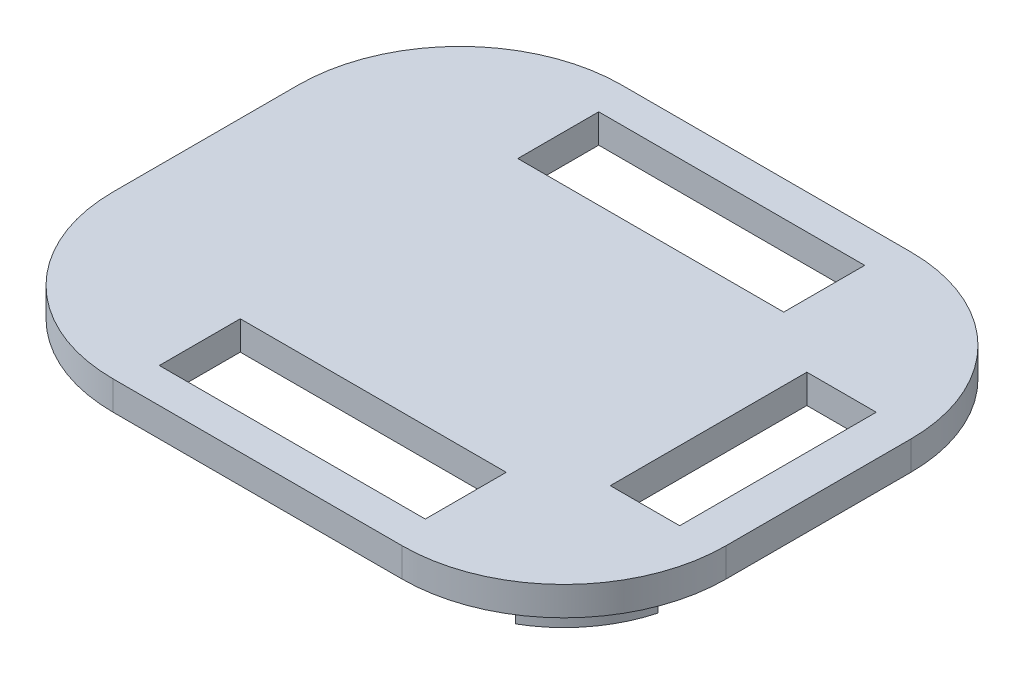
SolidWorks part; units mm, degrees
ref_plane "Front Plane" through (0, 0, 0) normal (0, 0, 1) x (1, 0, 0)
ref_plane "Top Plane" through (0, 0, 0) normal (0, 1, 0) x (1, 0, 0)
ref_plane "Right Plane" through (0, 0, 0) normal (1, 0, 0) x (0, 0, -1)
sketch "Sketch1" plane through (0, 0, 0) normal (0, 1, 0) x (1, 0, 0)
  line L4 (-26.5, 8) -> (-26.5, -8) construction
  line L6 (26.5, -8) -> (26.5, 8) construction
  line L8 (-6.9007, 0) -> (7.9319, 0) construction
  line L9 (0, 7.9961) -> (0, -5.1117) construction
  line L10 (-11.5, -12) -> (11.5, -12)
  line L11 (17, 8.5) -> (23, 8.5)
  line L12 (17, 8.5) -> (17, -8.5)
  line L13 (17, -8.5) -> (23, -8.5)
  line L14 (23, 8.5) -> (23, -8.5)
  line L15 (17, 8.5) -> (23, -8.5) construction
  line L16 (17, -8.5) -> (23, 8.5) construction
  line L17 (-11.5, 19) -> (11.5, 19)
  line L18 (-11.5, 19) -> (-11.5, 12)
  line L19 (-11.5, 12) -> (11.5, 12)
  line L20 (11.5, 19) -> (11.5, 12)
  line L21 (-11.5, 19) -> (11.5, 12) construction
  line L22 (-11.5, 12) -> (11.5, 19) construction
  line L23 (11.5, -19) -> (11.5, -12)
  line L24 (-11.5, -19) -> (11.5, -19)
  line L25 (-11.5, -19) -> (-11.5, -12)
  line L26 (-26.5, 8) -> (-26.5, -8)
  line L27 (-12.5, -22) -> (12.5, -22)
  line L28 (26.5, -8) -> (26.5, 8)
  line L29 (12.5, 22) -> (-12.5, 22)
  arc A6 (12.5, -22) -> (26.5, -8) centre (12.5, -8) ccw construction
  arc A7 (26.5, 8) -> (12.5, 22) centre (12.5, 8) ccw construction
  arc A8 (-12.5, 22) -> (-26.5, 8) centre (-12.5, 8) ccw
  arc A9 (-26.5, -8) -> (-12.5, -22) centre (-12.5, -8) ccw
  arc A10 (12.5, -22) -> (26.5, -8) centre (12.5, -8) ccw
  arc A11 (26.5, 8) -> (12.5, 22) centre (12.5, 8) ccw
  point P3 (26.5, 0)
  point P29 (20, 0)
  point P34 (0, 15.5)
  dimension "D3" = 16
  dimension "D4" = 14
  dimension "D2" = 25
  dimension "D7" = 17
  dimension "D8" = 6
  dimension "D9" = 20
  dimension "D10" = 23
  dimension "D11" = 7
  dimension "D12" = 15.5
extrude "Boss-Extrude1" add sketch "Sketch1" along normal blind 2.5
sketch "Sketch2" plane through (0, 0, 0) normal (0, -1, 0) x (1, 0, 0)
  line L0 (-12.5, -19.5) -> (12.5, -19.5) construction
  line L1 (24, -8) -> (24, 8) construction
  line L2 (12.5, 19.5) -> (-12.5, 19.5) construction
  line L3 (-24, 8) -> (-24, -8) construction
  line L4 (-12.5, -22) -> (12.5, -22)
  line L5 (26.5, -8) -> (26.5, 8)
  line L6 (12.5, 22) -> (-12.5, 22)
  line L7 (-26.5, 8) -> (-26.5, -8)
  line L8 (-12.5, -22) -> (12.5, -22) construction
  line L9 (26.5, -8) -> (26.5, 8) construction
  line L10 (12.5, 22) -> (-12.5, 22) construction
  line L11 (-26.5, 8) -> (-26.5, -8) construction
  line L12 (-12.5, -17) -> (12.5, -17) construction
  line L13 (21.5, -8) -> (21.5, 8) construction
  line L14 (12.5, 17) -> (-12.5, 17) construction
  line L15 (-21.5, 8) -> (-21.5, -8) construction
  line L16 (-17, 15.7942) -> (-18.25, 17.9593)
  line L17 (0, 7.0039) -> (0, -4.9946) construction
  line L18 (-8.9558, 0) -> (14.467, 0) construction
  line L19 (-23.6081, 10.9764) -> (-21.1933, 10.3294)
  line L20 (-12.5, 8) -> (-17, 15.7942) construction
  line L21 (-21.1933, 10.3294) -> (-12.5, 8) construction
  line L22 (23.6081, 10.9764) -> (21.1933, 10.3294)
  line L23 (17, 15.7942) -> (18.25, 17.9593)
  line L24 (17, -15.7942) -> (18.25, -17.9593)
  line L25 (23.6081, -10.9764) -> (21.1933, -10.3294)
  line L26 (-23.6081, -10.9764) -> (-21.1933, -10.3294)
  line L27 (-17, -15.7942) -> (-18.25, -17.9593)
  arc A0 (-24, -8) -> (-12.5, -19.5) centre (-12.5, -8) ccw construction
  arc A1 (12.5, -19.5) -> (24, -8) centre (12.5, -8) ccw construction
  arc A2 (24, 8) -> (12.5, 19.5) centre (12.5, 8) ccw construction
  arc A3 (-18.25, 17.9593) -> (-23.6081, 10.9764) centre (-12.5, 8) ccw
  arc A4 (-26.5, -8) -> (-12.5, -22) centre (-12.5, -8) ccw
  arc A5 (12.5, -22) -> (26.5, -8) centre (12.5, -8) ccw
  arc A6 (26.5, 8) -> (12.5, 22) centre (12.5, 8) ccw
  arc A7 (-12.5, 22) -> (-26.5, 8) centre (-12.5, 8) ccw
  arc A8 (-26.5, -8) -> (-12.5, -22) centre (-12.5, -8) ccw construction
  arc A9 (12.5, -22) -> (26.5, -8) centre (12.5, -8) ccw construction
  arc A10 (26.5, 8) -> (12.5, 22) centre (12.5, 8) ccw construction
  arc A11 (-12.5, 22) -> (-26.5, 8) centre (-12.5, 8) ccw construction
  arc A12 (-21.5, -8) -> (-12.5, -17) centre (-12.5, -8) ccw construction
  arc A13 (12.5, -17) -> (21.5, -8) centre (12.5, -8) ccw construction
  arc A14 (21.5, 8) -> (12.5, 17) centre (12.5, 8) ccw construction
  arc A15 (-17, 15.7942) -> (-21.1933, 10.3294) centre (-12.5, 8) ccw
  arc A16 (-23.6081, 10.9764) -> (-24, 8) centre (-12.5, 8) ccw construction
  arc A17 (-12.5, 19.5) -> (-24, 8) centre (-12.5, 8) ccw construction
  arc A18 (-21.1933, 10.3294) -> (-21.5, 8) centre (-12.5, 8) ccw construction
  arc A19 (-12.5, 17) -> (-21.5, 8) centre (-12.5, 8) ccw construction
  arc A20 (-12.5, 19.5) -> (-18.25, 17.9593) centre (-12.5, 8) ccw construction
  arc A21 (-12.5, 17) -> (-17, 15.7942) centre (-12.5, 8) ccw construction
  arc A22 (17, 15.7942) -> (21.1933, 10.3294) centre (12.5, 8) cw
  arc A23 (18.25, 17.9593) -> (23.6081, 10.9764) centre (12.5, 8) cw
  arc A24 (18.25, -17.9593) -> (23.6081, -10.9764) centre (12.5, -8) ccw
  arc A25 (17, -15.7942) -> (21.1933, -10.3294) centre (12.5, -8) ccw
  arc A26 (-17, -15.7942) -> (-21.1933, -10.3294) centre (-12.5, -8) cw
  arc A27 (-18.25, -17.9593) -> (-23.6081, -10.9764) centre (-12.5, -8) cw
  dimension "D4" = 45
  dimension "D5" = 15
  dimension "D1" = 0
  dimension "D2" = 2.5
  dimension "D3" = 2.5
extrude "Boss-Extrude2" add sketch "Sketch2" along normal blind 2.5
